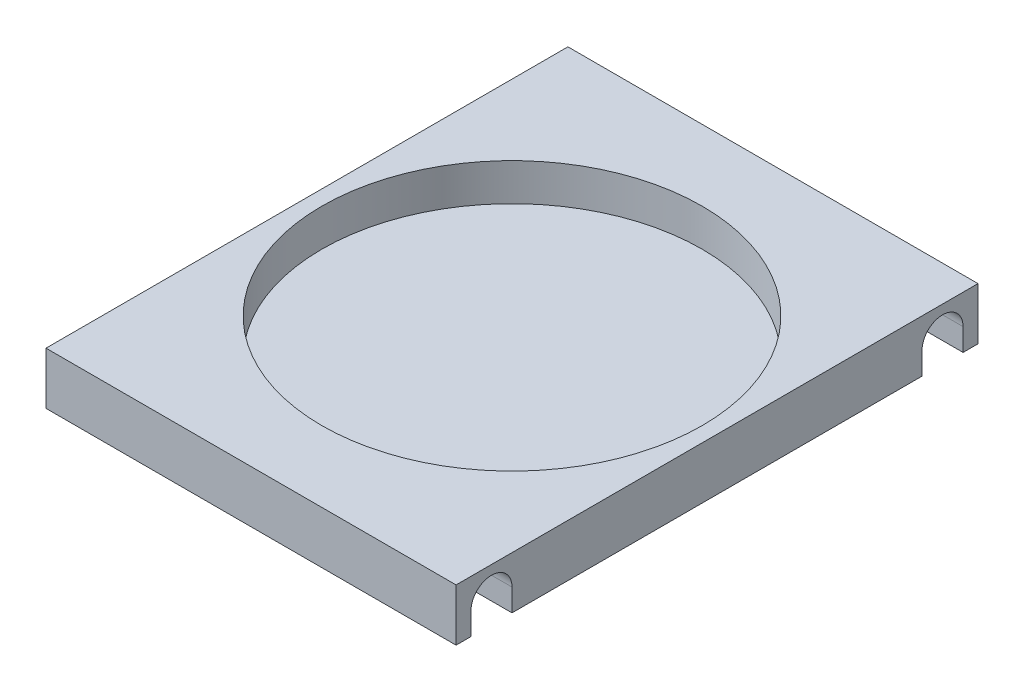
SolidWorks part; units mm, degrees
ref_plane "Front Plane" through (0, 0, 0) normal (0, 0, 1) x (1, 0, 0)
ref_plane "Top Plane" through (0, 0, 0) normal (0, 1, 0) x (1, 0, 0)
ref_plane "Right Plane" through (0, 0, 0) normal (1, 0, 0) x (0, 0, -1)
sketch "Sketch2" plane through (0, 0, 0) normal (0, 1, 0) x (1, 0, 0)
  line L1 (-27.5, 35) -> (27.5, 35)
  line L2 (-27.5, 35) -> (-27.5, -35)
  line L3 (-27.5, -35) -> (27.5, -35)
  line L4 (27.5, 35) -> (27.5, -35)
  line L5 (-27.5, 35) -> (27.5, -35) construction
  line L6 (-27.5, -35) -> (27.5, 35) construction
  point P0 (0, 0)
  dimension "D1" = 55
  dimension "D2" = 70
extrude "Boss-Extrude1" add sketch "Sketch2" along normal blind 8
sketch "Sketch3" plane through (0, 8, 0) normal (0, 1, 0) x (1, 0, 0)
  circle A0 centre (0, 0) radius 25.5
  dimension "D1" = 51
extrude "Cut-Extrude1" cut sketch "Sketch3" against normal blind 5
sketch "Sketch4" plane through (27.5, 0, 0) normal (1, 0, 0) x (0, 0, -1)
  line L0 (-35, 8) -> (-25.5, 8) construction
  line L1 (-30.25, 8) -> (-30.25, 0)
  line L2 (-35, 0) -> (35, 0) construction
  line L3 (-27.5, 4) -> (-27.5, 0)
  line L4 (-33, 4) -> (-33, 0)
  line L5 (-33, 0) -> (-27.5, 0)
  circle A0 centre (-30.25, 4) radius 2.75
  line M1 (-35, 0) -> (35, 0)
  dimension "D1" = 5.5
extrude "Cut-Extrude3" cut sketch "Sketch4" against normal blind 125 contours A0 L4 L1 M1 | A0 L1 L3 M1 | A0 L1 | L1 A0
sketch "Sketch5" plane through (27.5, 0, 0) normal (1, 0, 0) x (0, 0, -1)
  line L0 (0, 8) -> (0, 0) construction
  line L1 (-35, 8) -> (35, 8) construction
ref_plane "Plane1" through (0, 0, 0) normal (0, 0, 1) x (0, -1, 0)
mirror "Mirror1" about plane through (0, 0, 0) normal (0, 0, 1) of "Cut-Extrude3"
sketch "Sketch6" plane through (27.5, 0, 0) normal (1, 0, 0) x (0, 0, -1)
  line L0 (35, 8) -> (35, 0) construction
  line L1 (-35, 0) -> (35, 0)
  line L2 (-35, 0) -> (-35, 1)
  line L3 (-35, 1) -> (35, 1)
  line L4 (35, 0) -> (35, 1)
  dimension "D1" = 1
extrude "Cut-Extrude4" cut sketch "Sketch6" against normal blind 125
